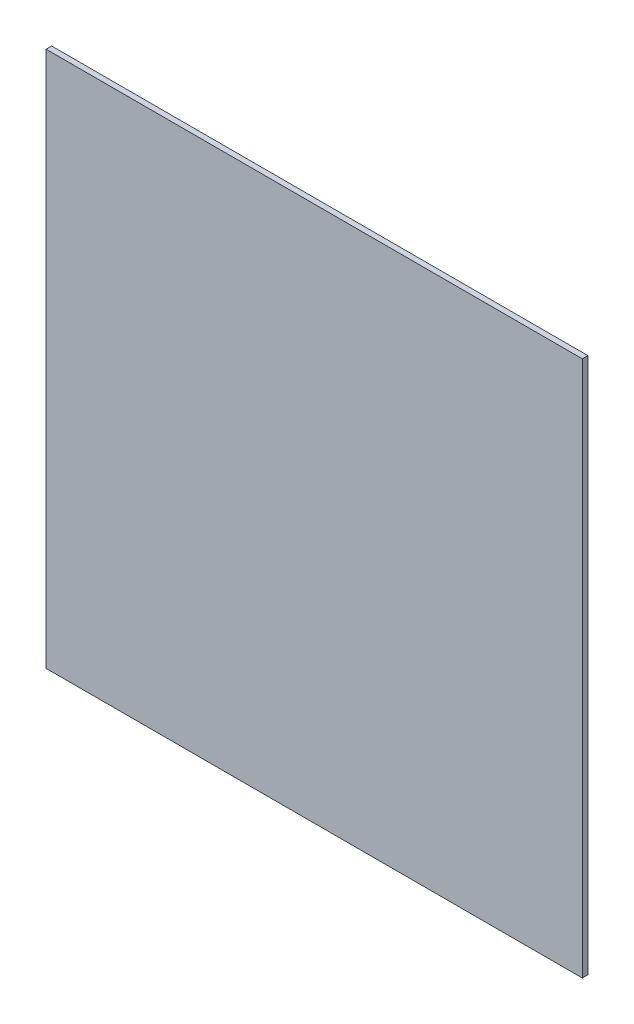
SolidWorks part; units mm, degrees
ref_plane "Front Plane" through (0, 0, 0) normal (0, 0, 1) x (1, 0, 0)
ref_plane "Top Plane" through (0, 0, 0) normal (0, 1, 0) x (1, 0, 0)
ref_plane "Right Plane" through (0, 0, 0) normal (1, 0, 0) x (0, 0, -1)
sketch "Sketch1" plane through (0, 0, 0) normal (0, 0, 1) x (1, 0, 0)
  line L1 (-66.1459, 47.3734) -> (86.2541, 47.3734)
  line L2 (-66.1459, 47.3734) -> (-66.1459, -105.0266)
  line L3 (-66.1459, -105.0266) -> (86.2541, -105.0266)
  line L4 (86.2541, 47.3734) -> (86.2541, -105.0266)
  dimension "D1" = 152.4
  dimension "D2" = 152.4
extrude "Boss-Extrude1" add sketch "Sketch1" along normal blind 1.5875
